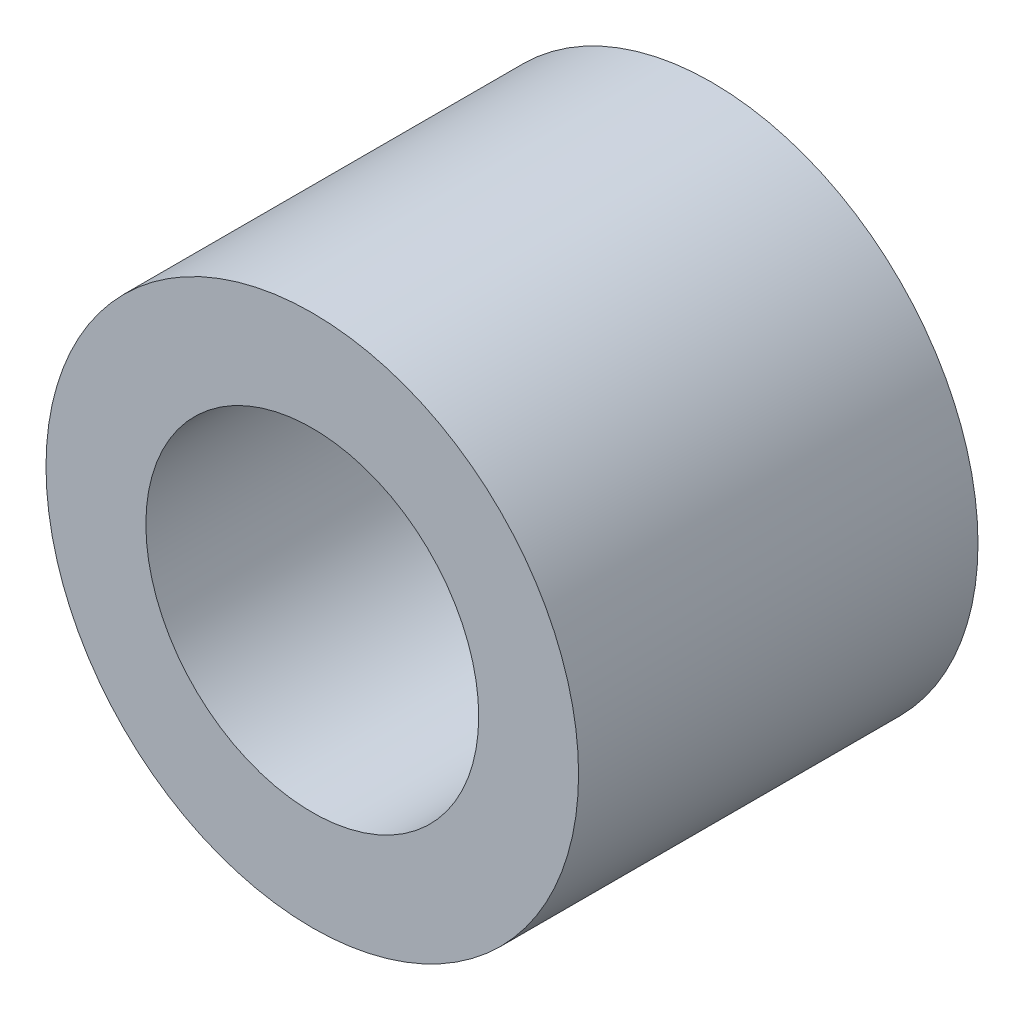
SolidWorks part; units mm, degrees
material "Brass"
ref_plane "Front Plane" through (0, 0, 0) normal (0, 0, 1) x (1, 0, 0)
ref_plane "Top Plane" through (0, 0, 0) normal (0, 1, 0) x (1, 0, 0)
ref_plane "Right Plane" through (0, 0, 0) normal (1, 0, 0) x (0, 0, -1)
sketch "Sketch1" plane through (0, 0, 0) normal (0, 0, 1) x (1, 0, 0)
  circle A0 centre (0, 0) radius 4
  circle A1 centre (0, 0) radius 2.5
  dimension "D1" = 5
  dimension "D2" = 8
extrude "Boss-Extrude1" add sketch "Sketch1" along normal blind 6
